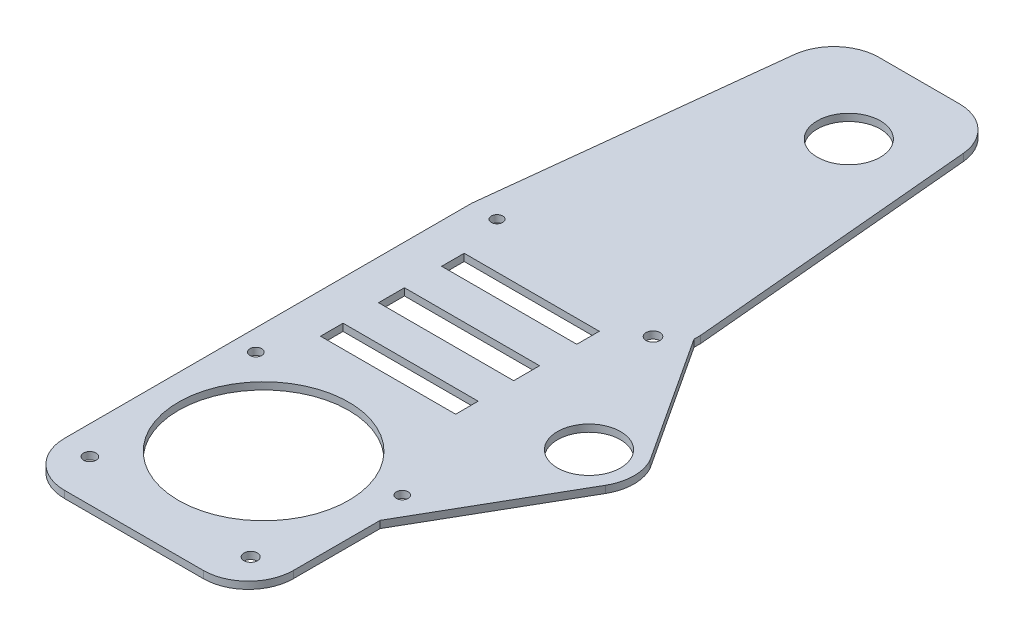
SolidWorks part; units mm, degrees
ref_plane "Front" through (0, 0, 0) normal (0, 0, 1) x (1, 0, 0)
ref_plane "Top" through (0, 0, 0) normal (0, 1, 0) x (1, 0, 0)
ref_plane "Right" through (0, 0, 0) normal (1, 0, 0) x (0, 0, -1)
sketch "Sketch1" plane through (0, 0, 0) normal (0, 1, 0) x (1, 0, 0)
  line L0 (10.4543, 228.6) -> (0, 135.3627)
  line L1 (0, 0) -> (50.8, 0)
  line L2 (0, 0) -> (0, 228.6)
  line L3 (0, 228.6) -> (50.8, 228.6)
  line L4 (50.8, 0) -> (50.8, 228.6)
  line L5 (42.3273, 228.6) -> (50.8, 135.3627)
  line L8 (50.8, 0) -> (24.327, 0)
  line L9 (50.8, 0) -> (50.8, -15)
  line L16 (50.8, 120.6192) -> (50.8, 104.4882)
  line L18 (50.8, 64.8791) -> (50.8, 87.4235)
  circle A12 centre (60.4, 101.001) radius 10
  circle A13 centre (29.5042, 189.5572) radius 7
  circle A15 centre (24.1018, 108.7849) radius 2.875
  dimension "D3" = 20
  dimension "D5" = 15
  dimension "D6" = 14
  dimension "D7" = 119.8151
  dimension "D1" = 50.8
  dimension "D2" = 228.6
extrude "Boss-Extrude1" add sketch "Sketch1" along normal blind 24.5875 contours L1 L4 L3 L0 L2
sketch "Sketch4" plane through (0, 0, -228.6) normal (0, 0, -1) x (-1, 0, 0)
  line L1 (-61.3109, 11.9192) -> (4.9615, 11.9192)
  line L2 (-61.3109, 11.9192) -> (-61.3109, -15.8811)
  line L3 (-61.3109, -15.8811) -> (4.9615, -15.8811)
  line L4 (4.9615, 11.9192) -> (4.9615, -15.8811)
extrude "Cut-Extrude2" cut sketch "Sketch4" against normal blind 20
fillet "Fillet3" radius 10 1 edges at (44.1447, 5.9596, -208.6)
fillet "Fillet4" radius 10 3 edges at (50.8, 12.2938, 0) (0, 12.2938, 0) (8.2118, 5.9596, -208.6)
sketch "Sketch6" plane through (0, 24.5875, 0) normal (0, 1, 0) x (1, 0, 0)
  line L0 (68.8909, 106.2834) -> (50.8, 135.3627)
  line L1 (50.8, 135.3627) -> (50.8, 103.801)
  line L2 (69.2582, 96.3607) -> (50.8, 61.1242)
  line L3 (50.8, 10) -> (50.8, 98.201) construction
  line L4 (50.8, 61.1242) -> (50.8, 96.3607)
  line L5 (50.8, 96.3607) -> (50.8, 98.201)
  circle A0 centre (60.4, 101.001) radius 10
extrude "Boss-Extrude3" add sketch "Sketch6" against normal blind 1.5875
sketch "Sketch7" plane through (0, 24.5875, 0) normal (0, 1, 0) x (1, 0, 0)
  circle A0 centre (60.4, 101.001) radius 7
  dimension "D1" = 14
extrude "Cut-Extrude3" cut sketch "Sketch7" against normal blind 1.5875
sketch "Sketch8" plane through (0, 24.5875, 0) normal (0, 1, 0) x (1, 0, 0)
  line L0 (35.0123, 208.6) -> (17.1532, 208.6) construction
  line L1 (9.492, 121.9099) -> (34.9257, 121.9099)
  line L2 (9.492, 121.9099) -> (9.492, 115.9099)
  line L3 (9.492, 115.9099) -> (34.9257, 115.9099)
  line L4 (34.9257, 121.9099) -> (34.9257, 115.9099)
  line L5 (9.492, 134.7849) -> (34.9257, 134.7849)
  line L6 (9.492, 134.7849) -> (9.492, 129.7849)
  line L7 (9.492, 129.7849) -> (34.9257, 129.7849)
  line L8 (34.9257, 134.7849) -> (34.9257, 129.7849)
  line L9 (9.492, 107.7849) -> (34.9257, 107.7849)
  line L10 (9.492, 107.7849) -> (9.492, 102.7849)
  line L11 (9.492, 102.7849) -> (34.9257, 102.7849)
  line L12 (34.9257, 107.7849) -> (34.9257, 102.7849)
  circle A0 centre (9.492, 118.9099) radius 3
  circle A1 centre (34.9257, 118.9099) radius 3
  circle A2 centre (23.3804, 122.2849) radius 2.5
  circle A4 centre (24.1018, 108.7849) radius 2.875 construction
  circle A5 centre (9.492, 132.2849) radius 2.5
  circle A6 centre (34.9257, 132.2849) radius 2.5
  circle A7 centre (24.29, 95.2849) radius 2.5
  circle A8 centre (24.1018, 108.7849) radius 2.875 construction
  circle A9 centre (9.492, 105.2849) radius 2.5
  circle A10 centre (34.9257, 105.2849) radius 2.5
  circle A11 centre (24.5838, 64.5939) radius 18.9
  circle M15 centre (24.1018, 108.7849) radius 2.875
  dimension "D1" = 13.5
  dimension "D2" = 13.5
  dimension "D3" = 73.8151
extrude "Cut-Extrude4" cut sketch "Sketch8" against normal blind 10 contours A1 L1 A0 L3 M15 | L2 A0 | L2 A0 | M15 | L4 A1 | L4 A1 | A5 L7 A2 L5 | A9 L11 A7 L9 | A10 L9 A7 L11 | A7 | A6
sketch "Sketch9" plane through (0, 0, 0) normal (0, -1, 0) x (1, 0, 0)
  line L1 (134.4567, -306.3857) -> (-94.6503, -306.3857)
  line L2 (134.4567, -306.3857) -> (134.4567, 54.8813)
  line L3 (134.4567, 54.8813) -> (-94.6503, 54.8813)
  line L4 (-94.6503, -306.3857) -> (-94.6503, 54.8813)
  circle A0 centre (6.3356, -44.2888) radius 1.3882
  circle A1 centre (43.4477, -42.8684) radius 1.4834
  circle A2 centre (4.6595, -82.7932) radius 1.3149
  circle A3 centre (48.401, -71.551) radius 1.2486
  circle A4 centre (5.8847, -135.1031) radius 1.2556
  circle A5 centre (45.7477, -129.8635) radius 1.5391
extrude "Cut-Extrude5" cut sketch "Sketch9" against normal blind 13
sketch "Sketch10" plane through (0, 24.5875, 0) normal (0, 1, 0) x (1, 0, 0)
  line L1 (8.7856, 124.9149) -> (38.774, 124.9149)
  line L2 (8.7856, 124.9149) -> (8.7856, 119.9149)
  line L3 (8.7856, 119.9149) -> (38.774, 119.9149)
  line L4 (38.774, 124.9149) -> (38.774, 119.9149)
  line L5 (8.7856, 111.6599) -> (38.774, 111.6599)
  line L6 (8.7856, 111.6599) -> (8.7856, 105.9099)
  line L7 (8.7856, 105.9099) -> (38.774, 105.9099)
  line L8 (38.774, 111.6599) -> (38.774, 105.9099)
  line L9 (8.7856, 98.0289) -> (38.774, 98.0289)
  line L10 (8.7856, 98.0289) -> (8.7856, 93.0289)
  line L11 (8.7856, 93.0289) -> (38.774, 93.0289)
  line L12 (38.774, 98.0289) -> (38.774, 93.0289)
  circle A0 centre (23.841, 122.4149) radius 2.5
  circle A1 centre (24.1018, 108.7849) radius 2.875 construction
  circle A2 centre (23.841, 95.5289) radius 2.5
  circle M1 centre (9.492, 118.9099) radius 3
  dimension "D1" = 13.63
extrude "Cut-Extrude6" cut sketch "Sketch10" against normal blind 22 contours A0 L1 L2 L3 M1 | A0 L3 L4 L1 | A0 | L8 L5 L6 L7 | A2 L9 L10 L11 | A2 L11 L12 L9 | A2 | L2 L3 M1
sketch "Sketch11" plane through (0, 24.5875, 0) normal (0, 1, 0) x (1, 0, 0)
  circle A0 centre (8.5355, 118.295) radius 5.2367
extrude "Cut-Extrude7" cut sketch "Sketch11" against normal blind 10
sketch "Sketch12" plane through (0, 14.5875, 0) normal (0, 1, 0) x (1, 0, 0)
  line L0 (50.8, 133.9005) -> (69.1954, 105.7592)
  line L1 (50.8, 103.801) -> (50.8, 135.3627) construction
  line L2 (69.0677, 96.0139) -> (50.8, 64.2642)
  line L3 (50.8, 10) -> (50.8, 98.201) construction
  line L4 (50.8, 64.2642) -> (50.8, 98.201)
  line L5 (50.8, 133.9005) -> (50.8, 103.801)
  circle A0 centre (60.4, 101.001) radius 10
  line M24 (50.8, 10) -> (50.8, 98.201)
  arc M25 (50.8, 98.201) -> (50.8, 103.801) centre (60.4, 101.001) cw
  line M26 (50.8, 103.801) -> (50.8, 135.3627)
extrude "Boss-Extrude4" add sketch "Sketch12" against normal blind 1.59 contours A0 L0 M26 | L0 A0 M25 | A0 L2 M24
sketch "Sketch13" plane through (0, 14.5875, 0) normal (0, 1, 0) x (1, 0, 0)
  circle A0 centre (60.4, 101.001) radius 7
extrude "Cut-Extrude8" cut sketch "Sketch13" against normal blind 41
sketch "Sketch14" plane through (0, 0, -228.6) normal (0, 0, -1) x (-1, 0, 0)
  line L1 (-2.551, 39.1752) -> (-64.0429, 39.1752)
  line L2 (-2.551, 39.1752) -> (-2.551, 3.5877)
  line L3 (-2.551, 3.5877) -> (-64.0429, 3.5877)
  line L4 (-64.0429, 39.1752) -> (-64.0429, 3.5877)
extrude "Cut-Extrude9" cut sketch "Sketch14" against normal blind 20
fillet "Fillet5" radius 10 2 edges at (8.2118, 13.7938, -208.6) (44.1447, 13.7938, -208.6)
sketch "Sketch16" plane through (0, 0, 0) normal (0, 0, 1) x (1, 0, 0)
  line L1 (-74.9257, 20.893) -> (88.7974, 20.893)
  line L2 (-74.9257, 20.893) -> (-74.9257, -1.979)
  line L3 (-74.9257, -1.979) -> (88.7974, -1.979)
  line L4 (88.7974, 20.893) -> (88.7974, -1.979)
extrude "Cut-Extrude11" cut sketch "Sketch16" against normal blind 35
fillet "Fillet6" radius 10 2 edges at (50.8, 13.7938, -35) (0, 13.7938, -35)
sketch "Sketch17" plane through (0, 0, 0) normal (0, -1, 0) x (1, 0, 0)
  circle A0 centre (45.7477, -129.8635) radius 1.5391
  circle A1 centre (5.8847, -135.1031) radius 1.2556
  circle A2 centre (48.401, -71.551) radius 1.3
  circle A3 centre (4.6595, -82.7932) radius 1.3149
  circle A4 centre (6.3356, -44.2888) radius 1.3882
  circle A5 centre (43.4477, -42.8684) radius 1.5
extrude "Cut-Extrude12" cut sketch "Sketch17" against normal blind 42
sketch "Sketch18" plane through (0, 24.5875, 0) normal (0, 1, 0) x (1, 0, 0)
  circle A0 centre (24.5838, 64.5939) radius 18.9
extrude "Cut-Extrude13" cut sketch "Sketch18" against normal blind 30
equation "\"7i\"=101.6"
